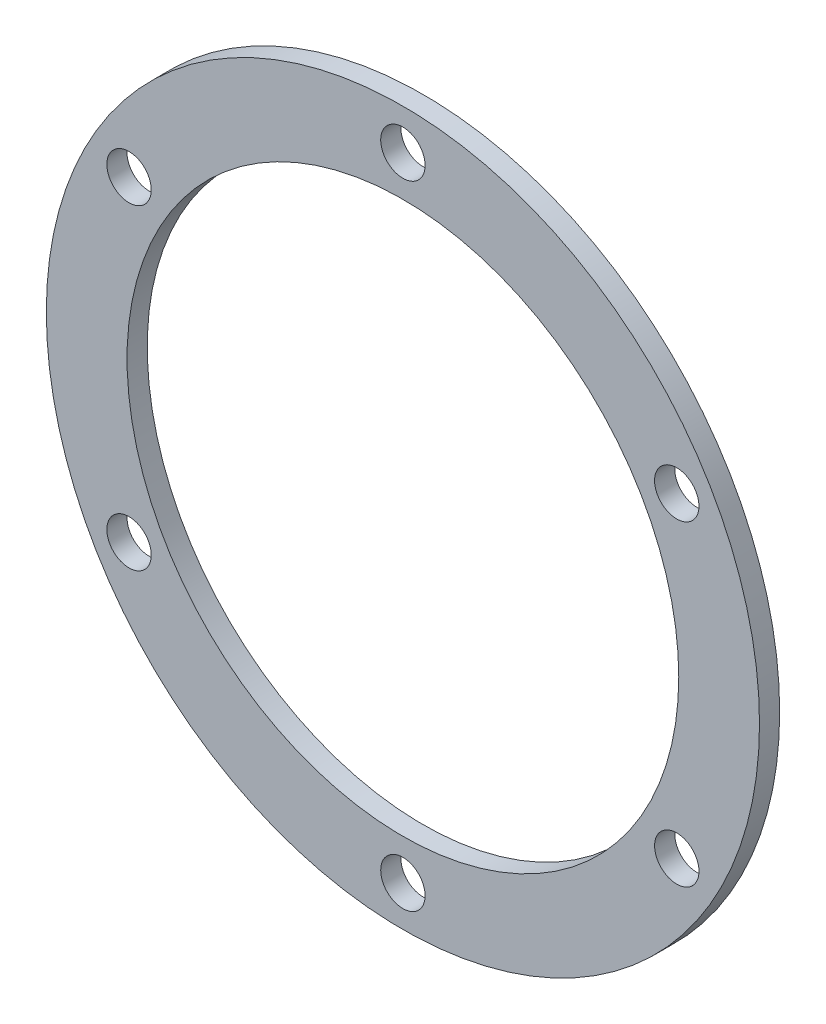
SolidWorks part; units mm, degrees
material "ABS"
ref_plane "前视基准面" through (0, 0, 0) normal (0, 0, 1) x (1, 0, 0)
ref_plane "上视基准面" through (0, 0, 0) normal (0, 1, 0) x (1, 0, 0)
ref_plane "右视基准面" through (0, 0, 0) normal (1, 0, 0) x (0, 0, -1)
other "Configuration Table"
sketch "草图1" plane through (0, 0, 0) normal (0, 0, 1) x (1, 0, 0)
  circle A0 centre (0, 0) radius 20.5
  circle A1 centre (0, 0) radius 26.5
  dimension "D1" = 41
  dimension "D2" = 6
extrude "凸台-拉伸1" add sketch "草图1" along normal blind 1.5
sketch "草图2" plane through (0, 0, 1.5) normal (0, 0, 1) x (1, 0, 0)
  circle A0 centre (0, 0) radius 23.5 construction
  circle A1 centre (0, 0) radius 20.5 construction
  circle A2 centre (0, 23.5) radius 1.65
  dimension "D1" = 3
  dimension "D2" = 3.3
extrude "切除-拉伸1" cut sketch "草图2" against normal blind 1.5
pattern_circular "阵列(圆周)1" count 6 over 360 about axis through (0, 0, 0) along (0, 0, 1) of "切除-拉伸1"
